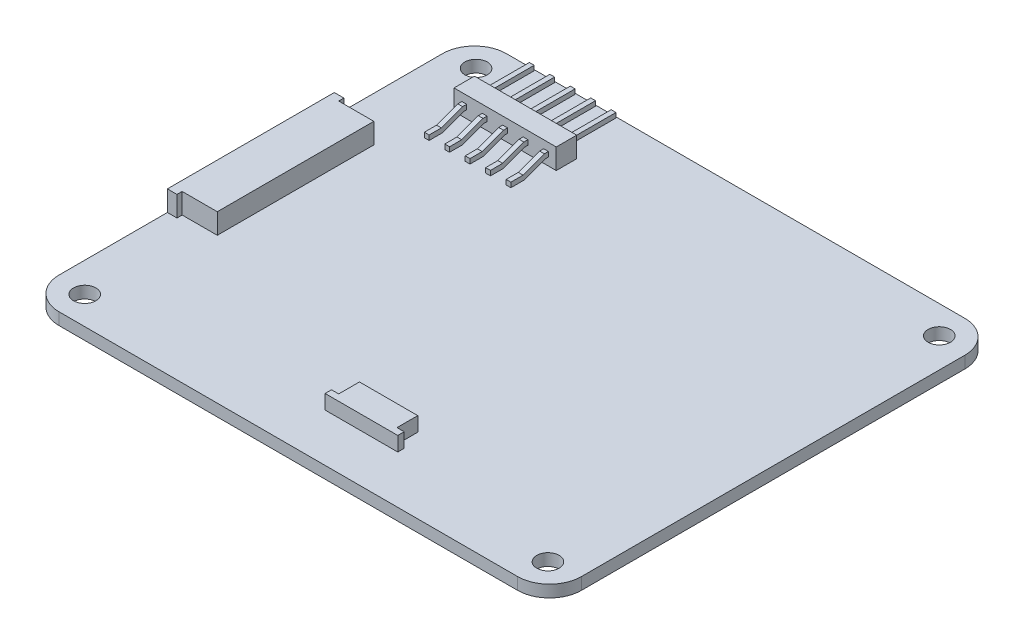
SolidWorks part; units mm, degrees
ref_plane "Plan de face" through (0, 0, 0) normal (0, 0, 1) x (1, 0, 0)
ref_plane "Plan de dessus" through (0, 0, 0) normal (0, 1, 0) x (1, 0, 0)
ref_plane "Plan de droite" through (0, 0, 0) normal (1, 0, 0) x (0, 0, -1)
sketch "Esquisse1" plane through (0, 0, 0) normal (0, 1, 0) x (1, 0, 0)
  line L1 (-32.7, 28) -> (32.7, 28)
  line L2 (-32.7, 28) -> (-32.7, -28)
  line L3 (-32.7, -28) -> (32.7, -28)
  line L4 (32.7, 28) -> (32.7, -28)
  line L5 (-32.7, 28) -> (32.7, -28) construction
  line L6 (-32.7, -28) -> (32.7, 28) construction
  point P0 (0, 0)
  dimension "D1" = 65.4
  dimension "D2" = 56
extrude "Boss.-Extru.1" add sketch "Esquisse1" along normal blind 1.5
fillet "Congé1" radius 4 4 edges at (32.7, 0.75, 28) (-32.7, 0.75, 28) (32.7, 0.75, -28) (-32.7, 0.75, -28)
sketch "Esquisse2" plane through (0, 1.5, 0) normal (0, 1, 0) x (1, 0, 0)
  line L1 (29, -24.5) -> (-29, -24.5) construction
  line L2 (29, -24.5) -> (29, 24.5) construction
  line L3 (29, 24.5) -> (-29, 24.5) construction
  line L4 (-29, -24.5) -> (-29, 24.5) construction
  line L5 (29, -24.5) -> (-29, 24.5) construction
  line L6 (29, 24.5) -> (-29, -24.5) construction
  circle A0 centre (-29, 24.5) radius 1.4
  circle A1 centre (-29, -24.5) radius 1.4
  circle A2 centre (29, -24.5) radius 1.4
  circle A3 centre (29, 24.5) radius 1.4
  point P0 (0, 0)
  dimension "D3" = 2.8
  dimension "D1" = 49
  dimension "D2" = 58
extrude "Enlèv. mat.-Extru.1" cut sketch "Esquisse2" against normal blind 1.5
sketch "Esquisse3" plane through (0, 1.5, 0) normal (0, 1, 0) x (1, 0, 0)
  line L0 (28.7, 28) -> (-28.7, 28) construction
  line L1 (-25.7, 21) -> (-12.9, 21)
  line L2 (-25.7, 21) -> (-25.7, 18.44)
  line L3 (-25.7, 18.44) -> (-12.9, 18.44)
  line L4 (-12.9, 21) -> (-12.9, 18.44)
  line L5 (-25.7, 21) -> (-12.9, 18.44) construction
  line L6 (-25.7, 18.44) -> (-12.9, 21) construction
  line L7 (-32.7, 24) -> (-32.7, -24) construction
  point P0 (-19.3, 19.72)
  dimension "D1" = 7
  dimension "D2" = 7
  dimension "D3" = 12.8
  dimension "D4" = 2.56
extrude "Boss.-Extru.2" add sketch "Esquisse3" along normal blind 2.56
sketch "Esquisse4" plane through (0, 1.5, 0) normal (0, 1, 0) x (1, 0, 0)
  line L1 (-24.72, 26.9) -> (-24.12, 26.9)
  line L2 (-24.72, 26.9) -> (-24.72, 13.74)
  line L3 (-24.72, 13.74) -> (-24.12, 13.74)
  line L4 (-24.12, 26.9) -> (-24.12, 13.74)
  line L5 (-24.72, 26.9) -> (-24.12, 13.74) construction
  line L6 (-24.72, 13.74) -> (-24.12, 26.9) construction
  line L7 (-12.9, 21) -> (-25.7, 21) construction
  line L8 (-25.7, 18.44) -> (-12.9, 18.44) construction
  line L9 (-25.7, 21) -> (-25.7, 18.44) construction
  line L10 (-21.56, 26.9) -> (-21.56, 13.74)
  line L11 (-22.16, 26.9) -> (-21.56, 26.9)
  line L12 (-22.16, 26.9) -> (-22.16, 13.74)
  line L13 (-22.16, 13.74) -> (-21.56, 13.74)
  line L14 (-19, 26.9) -> (-19, 13.74)
  line L15 (-19.6, 26.9) -> (-19, 26.9)
  line L16 (-19.6, 26.9) -> (-19.6, 13.74)
  line L17 (-19.6, 13.74) -> (-19, 13.74)
  line L18 (-16.44, 26.9) -> (-16.44, 13.74)
  line L19 (-17.04, 26.9) -> (-16.44, 26.9)
  line L20 (-17.04, 26.9) -> (-17.04, 13.74)
  line L21 (-17.04, 13.74) -> (-16.44, 13.74)
  line L22 (-13.88, 26.9) -> (-13.88, 13.74)
  line L23 (-14.48, 26.9) -> (-13.88, 26.9)
  line L24 (-14.48, 26.9) -> (-14.48, 13.74)
  line L25 (-14.48, 13.74) -> (-13.88, 13.74)
  line L26 (-24.12, 26.9) -> (-21.56, 26.9) construction
  point P0 (-24.42, 20.32)
  dimension "D1" = 5.9
  dimension "D2" = 4.7
  dimension "D3" = 0.6
  dimension "D4" = 1.28
  dimension "D6" = 2.56
  dimension "D5" = 5
extrude "Boss.-Extru.3" add sketch "Esquisse4" along normal blind 1.58
sketch "Esquisse5" plane through (-24.72, 0, 0) normal (-1, 0, 0) x (0, 0, 1)
  line L0 (-26.9, 3.08) -> (-26.9, 1.5) construction
  line L1 (-26.9, 2.48) -> (-21, 2.48)
  line L2 (-26.9, 2.48) -> (-26.9, 1.5)
  line L3 (-26.9, 1.5) -> (-21, 1.5)
  line L4 (-21, 2.48) -> (-21, 1.5)
  line L5 (-26.9, 3.08) -> (-21, 3.08) construction
  line L6 (-17.933, 3.08) -> (-15.2679, 2.1001)
  line L7 (-18.44, 3.08) -> (-13.74, 3.08) construction
  line L8 (-15.2679, 2.1001) -> (-13.74, 2.1001)
  line L9 (-13.74, 3.08) -> (-13.74, 1.5) construction
  line L10 (-13.3271, 3.2986) -> (-17.933, 3.4771)
  line L11 (-17.933, 3.4771) -> (-17.933, 3.08)
  line L12 (-18.44, 2.48) -> (-18.0398, 2.48)
  line L13 (-18.44, 3.08) -> (-18.44, 1.5) construction
  line L14 (-18.0398, 2.48) -> (-15.3745, 1.5)
  line L15 (-18.44, 1.5) -> (-13.74, 1.5) construction
  line L16 (-15.3745, 1.5) -> (-18.44, 1.5)
  line L17 (-18.44, 1.5) -> (-18.44, 2.48)
  line L18 (-24, 1.5) -> (24, 1.5) construction
  arc A0 (-13.74, 2.1001) -> (-13.3271, 3.2986) centre (-13.74, 2.7705) ccw
  dimension "D1" = 0.6
  dimension "D2" = 0.6001
  dimension "D3" = 0.6
extrude "Enlèv. mat.-Extru.2" cut sketch "Esquisse5" against normal up to surface (10.84 mm away) up to face at (-13.88, 2.29, -16.09)
sketch "Esquisse6" plane through (0, 1.5, 0) normal (0, 1, 0) x (1, 0, 0)
  line L0 (-32.7, 24) -> (-32.7, -24) construction
  line L1 (-31.5, 10.45) -> (-32.7, 10.45)
  line L2 (-27.1, 9.8) -> (-27.1, -9.8)
  line L3 (-31.5, -10.45) -> (-32.7, -10.45)
  line L4 (-32.7, 10.45) -> (-32.7, -10.45)
  line L5 (28.7, 28) -> (-28.7, 28) construction
  line L9 (-27.1, 9.8) -> (-31.5, 9.8)
  line L10 (-31.5, 10.45) -> (-31.5, 9.8)
  line L13 (-27.1, -9.8) -> (-31.5, -9.8)
  line L14 (-31.5, -10.45) -> (-31.5, -9.8)
  dimension "D1" = 5.6
  dimension "D2" = 20.9
  dimension "D3" = 17.55
  dimension "D4" = 19.6
  dimension "D5" = 0.65
  dimension "D6" = 1.2
  dimension "D7" = 1.2
extrude "Boss.-Extru.4" add sketch "Esquisse6" along normal blind 2.56
sketch "Esquisse7" plane through (0, 1.5, 0) normal (0, 1, 0) x (1, 0, 0)
  line L0 (-32.7, -10.45) -> (-32.7, -24) construction
  line L1 (-0.5, -18.6) -> (6.8, -18.6)
  line L2 (-0.5, -18.6) -> (-0.5, -21.2)
  line L4 (6.8, -18.6) -> (6.8, -21.2)
  line L5 (7.7, -21.2) -> (6.8, -21.2)
  line L6 (7.7, -21.2) -> (7.7, -22)
  line L7 (7.7, -22) -> (-1.4, -22)
  line L8 (-1.4, -21.2) -> (-1.4, -22)
  line L9 (28.7, 28) -> (-28.7, 28) construction
  line L10 (-0.5, -21.2) -> (-1.4, -21.2)
  dimension "D1" = 7.3
  dimension "D2" = 9.1
  dimension "D3" = 0.9
  dimension "D4" = 0.8
  dimension "D5" = 3.4
  dimension "D6" = 39.5
  dimension "D7" = 50
extrude "Boss.-Extru.5" add sketch "Esquisse7" along normal blind 1.8
